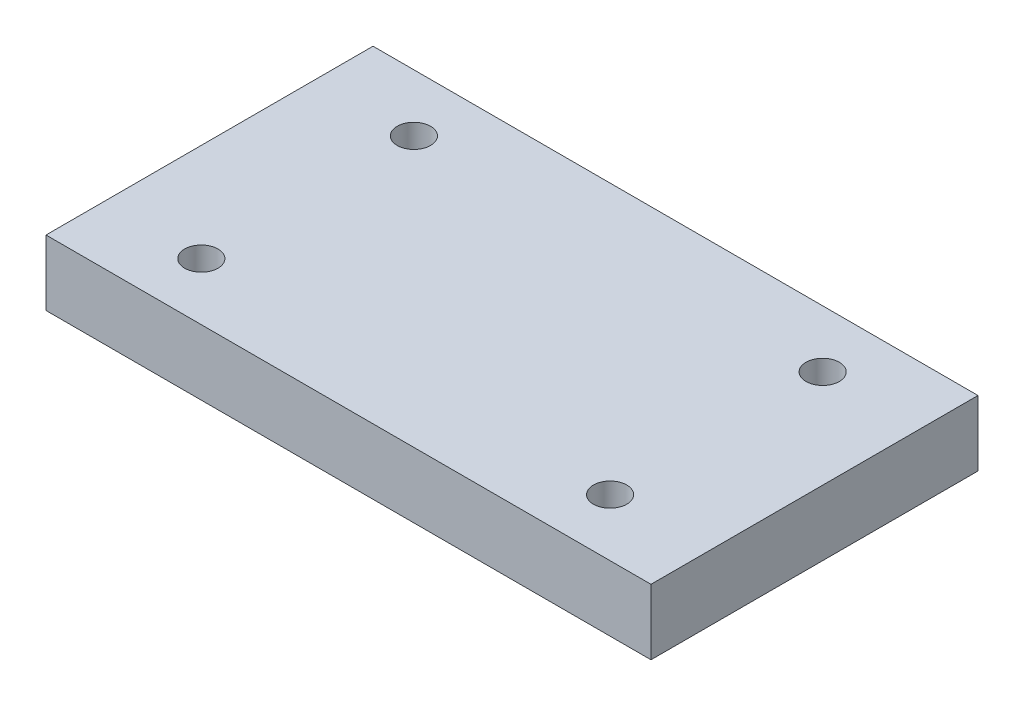
SolidWorks part; units mm, degrees
ref_plane "Front Plane" through (0, 0, 0) normal (0, 0, 1) x (1, 0, 0)
ref_plane "Top Plane" through (0, 0, 0) normal (0, 1, 0) x (1, 0, 0)
ref_plane "Right Plane" through (0, 0, 0) normal (1, 0, 0) x (0, 0, -1)
sketch "Sketch1" plane through (0, 0, 0) normal (0, 1, 0) x (1, 0, 0)
  line L1 (-92.5, -50) -> (92.5, -50)
  line L2 (-92.5, -50) -> (-92.5, 50)
  line L3 (-92.5, 50) -> (92.5, 50)
  line L4 (92.5, -50) -> (92.5, 50)
  line L5 (-92.5, -50) -> (92.5, 50) construction
  line L6 (-92.5, 50) -> (92.5, -50) construction
  point P0 (0, 0)
  point P14 (0, 0)
  point P15 (0, 0)
  point P16 (0, 0)
  point P17 (0, 0)
  dimension "D1" = 185
  dimension "D2" = 100
extrude "Boss-Extrude1" add sketch "Sketch1" along normal blind 20
hole_wizard "M12 Tapped Hole1" positions "Sketch2" profile "Sketch3" tap size "M12" standard "ISO" end condition up to next
sketch "Sketch2" plane through (0, 20, 0) normal (0, 1, 0) x (1, 0, 0)
  line L0 (92.5, 50) -> (-92.5, 50) construction
  line L1 (-92.5, -50) -> (92.5, -50) construction
  line L2 (-92.5, 50) -> (-92.5, -50) construction
  line L3 (92.5, -50) -> (92.5, 50) construction
  point P0 (-62.5, 32.5)
  point P2 (62.5, 32.5)
  point P4 (62.5, -32.5)
  point P6 (-62.5, -32.5)
  point P9 (0, 0)
  point P10 (0, 0)
  point P11 (0, 0)
  point P12 (0, 0)
  point P13 (0, 0)
  dimension "D1" = 17.5
  dimension "D2" = 17.5
  dimension "D3" = 30
  dimension "D4" = 30
sketch "Sketch3" plane through (-62.5, 20, -32.5) normal (1, 0, 0) x (0, 0, 1)
  line L0 (0, 0) -> (0, 20)
  line L1 (0, 20) -> (5.1, 20)
  line L2 (5.1, 20) -> (5.1, 0)
  line L5 (5.1, 0) -> (0, 0)
  line L11 (0, -6.35) -> (0, 107.95) construction
  dimension "Thru Tap Drill Dia." = 10.2
  dimension "Thru Tap Drill Depth" = 20
cosmetic thread "Hole Thread1" parameters "D2"=12
cosmetic thread "Hole Thread2" parameters "D2"=12
cosmetic thread "Hole Thread3" parameters "D2"=12
cosmetic thread "Hole Thread4" parameters "D2"=12
